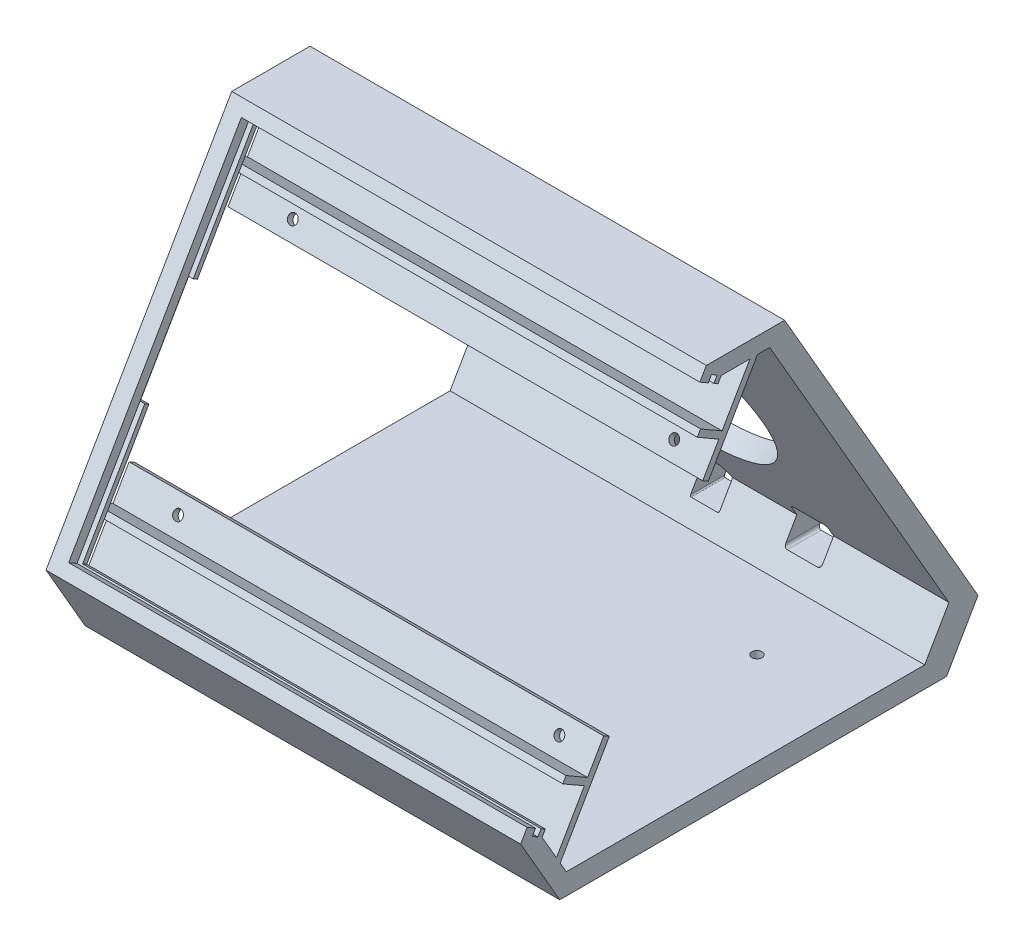
SolidWorks part; units mm, degrees
ref_plane "Front Plane" through (0, 0, 0) normal (0, 0, 1) x (1, 0, 0)
ref_plane "Top Plane" through (0, 0, 0) normal (0, 1, 0) x (1, 0, 0)
ref_plane "Right Plane" through (0, 0, 0) normal (1, 0, 0) x (0, 0, -1)
sketch "Sketch3" plane through (0, 0, 0) normal (1, 0, 0) x (0, 0, -1)
  line L0 (0, 0) -> (141, 0) construction
  line L1 (141, 0) -> (70.5, 122.1096) construction
  line L2 (70.5, 122.1096) -> (0, 0) construction
  line L3 (7.5, 12.9904) -> (15, 0)
  line L4 (7.5, 12.9904) -> (0, 0) construction
  line L5 (0, 0) -> (15, 0) construction
  line L6 (15, 0) -> (15, -1.5)
  line L7 (15, -1.5) -> (126, -1.5)
  line L8 (70.5, 122.1096) -> (70.5, 0) construction
  line L9 (133.5, 12.9904) -> (126, 0)
  line L10 (126, -1.5) -> (126, 0)
  line L11 (7.5, 12.9904) -> (6.201, 13.7404)
  line L12 (6.201, 13.7404) -> (61.701, 109.8692)
  line L13 (61.701, 109.8692) -> (63, 109.1192)
  line L14 (63, 109.1192) -> (78, 109.1192)
  line L15 (79.299, 109.8692) -> (134.799, 13.7404)
  line L16 (134.799, 13.7404) -> (133.5, 12.9904)
  line L17 (78, 109.1192) -> (79.299, 109.8692)
  line L18 (58.3812, 114.1192) -> (0.8605, 14.4904)
  line L19 (0.8605, 14.4904) -> (12.9793, -6.5)
  line L20 (12.9793, -6.5) -> (132.75, -6.5)
  line L21 (132.75, -6.5) -> (142.5042, 10.3947)
  line L22 (142.5042, 10.3947) -> (82.6188, 114.1192)
  line L23 (82.6188, 114.1192) -> (58.3812, 114.1192)
  line L24 (129.75, 6.4952) -> (137.6271, 1.9474) construction
  line L25 (70.5, -1.5) -> (70.5, -6.5) construction
  line L26 (78, 109.1192) -> (78, 114.1192) construction
  dimension "D1" = 141
  dimension "D2" = 1.5
  dimension "D3" = 111
  dimension "D4" = 15
  dimension "D5" = 5
  dimension "D6" = 5
  dimension "D7" = 5
  dimension "D8" = 5
  dimension "D9" = 5
  dimension "D10" = 9.0957
extrude "Boss-Extrude1" add sketch "Sketch3" along normal blind 155
sketch "Sketch4" plane through (0, 3.25, 5.6292) normal (0, 0.5, 0.866) x (1, 0, 0)
  line L0 (155, 126) -> (0, 126) construction
  line L1 (5.5, 126) -> (149.5, 126)
  line L2 (5.5, 126) -> (5.5, 15)
  line L3 (5.5, 15) -> (149.5, 15)
  line L4 (149.5, 126) -> (149.5, 15)
  line L5 (155, 15) -> (0, 15) construction
  line L6 (5.5, 70.5) -> (0, 70.5) construction
  line L7 (0, 128.0207) -> (0, 12.9793) construction
  line L8 (149.5, 70.5) -> (155, 70.5) construction
  line L9 (155, 128.0207) -> (155, 12.9793) construction
  dimension "D1" = 144
extrude "Cut-Extrude1" cut sketch "Sketch4" against normal up to surface (5 mm away) up to face at (77.5, 61.8048, -33.951)
sketch "Sketch5" plane through (0, 64.3048, -111.3792) normal (0, 0.5, -0.866) x (-1, 0, 0)
  line L0 (-155, -62.25) -> (-77.5, -2.3646) construction
  line L1 (-77.5, -2.3646) -> (-155, 57.5207) construction
  line L2 (0, 57.5207) -> (-77.5, -2.3646) construction
  line L3 (-77.5, -2.3646) -> (0, -62.25) construction
  circle A0 centre (-77.5, -2.3646) radius 38.5
  dimension "D1" = 77
extrude "Cut-Extrude2" cut sketch "Sketch5" against normal blind 10
sketch "Sketch6" plane through (155, 0, 0) normal (1, 0, 0) x (0, 0, -1)
  line L6 (82.6188, 114.1192) -> (58.3812, 114.1192)
  line L7 (58.3812, 114.1192) -> (0.8605, 14.4904)
  line L8 (0.8605, 14.4904) -> (12.9793, -6.5)
  line L9 (12.9793, -6.5) -> (132.75, -6.5)
  line L10 (132.75, -6.5) -> (142.5042, 10.3947)
  line L11 (142.5042, 10.3947) -> (82.6188, 114.1192)
  line L12 (82.6188, 114.1192) -> (58.3812, 114.1192)
  line L13 (58.3812, 114.1192) -> (0.8605, 14.4904)
  line L14 (0.8605, 14.4904) -> (12.9793, -6.5)
  line L15 (12.9793, -6.5) -> (132.75, -6.5)
  line L16 (132.75, -6.5) -> (142.5042, 10.3947)
  line L17 (142.5042, 10.3947) -> (82.6188, 114.1192)
  dimension "D1" = 0
extrude "Boss-Extrude2" add sketch "Sketch6" along normal blind 5 separate body
sketch "Sketch7" plane through (160, 0, 0) normal (1, 0, 0) x (0, 0, -1)
  line L2 (78, 109.1192) -> (63, 109.1192) construction
  line L4 (126, 0) -> (133.5, 12.9904) construction
  line L20 (7.5, 12.9904) -> (15, 0) construction
  line L23 (63, 109.1192) -> (7.5, 12.9904)
  line L24 (15, 0) -> (126, 0)
  line L25 (78, 109.1192) -> (63, 109.1192)
  line L26 (133.5, 12.9904) -> (78, 109.1192)
  line L27 (126, 0) -> (133.5, 12.9904)
  line L31 (7.5, 12.9904) -> (15, 0)
extrude "Cut-Extrude3" cut sketch "Sketch7" against normal blind 5
sketch "Sketch8" plane through (160, 0, 0) normal (1, 0, 0) x (0, 0, -1)
  line L0 (6.201, 13.7404) -> (61.701, 109.8692)
  line L1 (61.701, 109.8692) -> (59.9689, 110.8692)
  line L3 (59.9689, 110.8692) -> (4.4689, 14.7404)
  line L5 (4.4689, 14.7404) -> (6.201, 13.7404)
  dimension "D1" = 2
extrude "Cut-Extrude4" cut sketch "Sketch8" against normal blind 2.5
sketch "Sketch10" plane through (160, 0, 0) normal (1, 0, 0) x (0, 0, -1)
  line L0 (35.25, 61.0548) -> (29.6208, 64.3048) construction
  line L1 (63, 109.1192) -> (7.5, 12.9904) construction
  line L2 (58.3812, 114.1192) -> (0.8605, 14.4904) construction
  line L3 (42.75, 74.0452) -> (27.75, 48.0644)
  line L4 (27.75, 48.0644) -> (26.451, 48.8144)
  line L5 (6.201, 13.7404) -> (61.701, 109.8692) construction
  line L6 (26.451, 48.8144) -> (41.451, 74.7952)
  line L7 (42.75, 74.0452) -> (41.451, 74.7952)
  point P13 (33.951, 61.8048)
  dimension "D1" = 30
extrude "Cut-Extrude5" cut sketch "Sketch10" against normal blind 2.5
sketch "Sketch11" plane through (160, 0, 0) normal (1, 0, 0) x (0, 0, -1)
  line L0 (63, 109.1192) -> (62, 107.3872)
  line L1 (63, 109.1192) -> (42.75, 74.0452) construction
  line L2 (7.5, 12.9904) -> (8.5, 14.7224)
  line L3 (27.75, 48.0644) -> (7.5, 12.9904) construction
  line L4 (0.8605, 14.4904) -> (12.9793, -6.5) construction
  line L5 (7.5, 12.9904) -> (15, 0) construction
  line L6 (15, 0) -> (126, 0) construction
  line L7 (12.9793, -6.5) -> (132.75, -6.5) construction
  line L8 (126, 0) -> (133.5, 12.9904) construction
  line L9 (132.75, -6.5) -> (142.5042, 10.3947) construction
  line L10 (142.5042, 10.3947) -> (82.6188, 114.1192) construction
  line L11 (133.5, 12.9904) -> (78, 109.1192) construction
  line L12 (82.6188, 114.1192) -> (58.3812, 114.1192) construction
  line L13 (78, 109.1192) -> (63, 109.1192) construction
  line L14 (0.8605, 14.4904) -> (12.9793, -6.5)
  line L15 (7.5, 12.9904) -> (15, 0)
  line L16 (15, 0) -> (126, 0)
  line L17 (12.9793, -6.5) -> (132.75, -6.5)
  line L18 (126, 0) -> (133.5, 12.9904)
  line L19 (132.75, -6.5) -> (142.5042, 10.3947)
  line L20 (142.5042, 10.3947) -> (82.6188, 114.1192)
  line L21 (133.5, 12.9904) -> (78, 109.1192)
  line L22 (82.6188, 114.1192) -> (58.3812, 114.1192)
  line L23 (78, 109.1192) -> (63, 109.1192)
  line L24 (62, 107.3872) -> (60.701, 108.1372)
  line L25 (41.451, 74.7952) -> (61.701, 109.8692) construction
  line L26 (60.701, 108.1372) -> (61.701, 109.8692)
  line L27 (61.701, 109.8692) -> (59.9689, 110.8692)
  line L28 (59.9689, 110.8692) -> (58.9689, 109.1372)
  line L29 (59.9689, 110.8692) -> (4.4689, 14.7404) construction
  line L30 (58.9689, 109.1372) -> (56.3708, 110.6372)
  line L31 (58.3812, 114.1192) -> (0.8605, 14.4904) construction
  line L32 (56.3708, 110.6372) -> (58.3812, 114.1192)
  line L33 (8.5, 14.7224) -> (7.201, 15.4724)
  line L34 (6.201, 13.7404) -> (26.451, 48.8144) construction
  line L35 (7.201, 15.4724) -> (6.201, 13.7404)
  line L36 (6.201, 13.7404) -> (4.4689, 14.7404)
  line L37 (4.4689, 14.7404) -> (5.4689, 16.4724)
  line L38 (5.4689, 16.4724) -> (2.8708, 17.9724)
  line L39 (2.8708, 17.9724) -> (0.8605, 14.4904)
  dimension "D1" = 2
extrude "Boss-Extrude3" add sketch "Sketch11" along normal blind 142
sketch "Sketch12" plane through (0, 64.3048, -111.3792) normal (0, 0.5, -0.866) x (-1, 0, 0)
  line L0 (-232.5, -2.3646) -> (-155, -2.3646) construction
  line L1 (-155, -62.25) -> (-155, 57.5207) construction
  line L2 (-77.5, -2.3646) -> (-155, -2.3646) construction
  circle A0 centre (-232.5, -2.3646) radius 38.5
  circle A1 centre (-77.5, -2.3646) radius 38.5 construction
extrude "Cut-Extrude6" cut sketch "Sketch12" against normal up to next (6.5 mm away)
delete or keep bodies "Body-Delete1" type delete bodies bodies 103
sketch "Sketch13" plane through (155, 0, 0) normal (-1, 0, 0) x (0, 0, 1)
  line L0 (-26.5934, 30.6611) -> (-21.5934, 22.0009)
  line L3 (-21.5934, 22.0009) -> (-14.925, 25.8509)
  line L4 (-63, 109.1192) -> (-7.5, 12.9904) construction
  line L5 (-26.5934, 30.6611) -> (-28.3254, 29.6611)
  line L8 (-28.3254, 29.6611) -> (-13.1003, 3.2904)
  line L11 (-7.5, 12.9904) -> (-15, 0) construction
  line L12 (-14.925, 25.8509) -> (-13.925, 24.1188)
  line L13 (-13.925, 24.1188) -> (-20.5934, 20.2688)
  line L14 (-20.5934, 20.2688) -> (-11.9456, 5.2904)
  line L15 (-11.9456, 5.2904) -> (-13.1003, 3.2904)
  line L16 (-62.2434, 92.4087) -> (-55.575, 96.2587)
  line L17 (-62.2434, 92.4087) -> (-57.2434, 83.7485)
  line L18 (-57.2434, 83.7485) -> (-58.9754, 82.7485)
  line L19 (-58.9754, 82.7485) -> (-74.2006, 109.1192)
  line L20 (-55.575, 96.2587) -> (-56.575, 97.9908)
  line L21 (-56.575, 97.9908) -> (-63.2434, 94.1408)
  line L22 (-63.2434, 94.1408) -> (-71.8912, 109.1192)
  line L23 (-78, 109.1192) -> (-63, 109.1192) construction
  line L24 (-74.2006, 109.1192) -> (-71.8912, 109.1192)
  line L25 (-56.575, 97.9908) -> (-63, 109.1192) construction
  line L26 (-13.925, 24.1188) -> (-7.5, 12.9904) construction
  dimension "D1" = 10
  dimension "D2" = 2
  dimension "D3" = 81.3
  dimension "D4" = 7.7
extrude "Boss-Extrude4" add sketch "Sketch13" along direction (-1, 0, 0) on the side against the normal up to surface (147 mm away)
ref_plane "Plane1" through (0, 0, -150) normal (0, 0, 1) x (1, 0, 0)
sketch "Sketch14" plane through (0, 0, -150) normal (0, 0, 1) x (1, 0, 0)
  line L0 (234.6666, 5.5875) -> (226.437, 5.5875) construction
  line L1 (234.6666, 5.5875) -> (226.437, 5.5875)
  line L2 (235.0476, 12.0391) -> (235.0476, 5.9685)
  line L3 (226.056, 12.0391) -> (226.056, 5.9685)
  line L4 (265.2999, 6.0875) -> (255.8999, 6.0875)
  line L5 (254.8999, 7.0875) -> (254.8999, 15.5875)
  line L7 (255.8999, 16.5875) -> (265.2999, 16.5875)
  line L8 (266.2999, 15.5875) -> (266.2999, 7.0875)
  line L9 (265.7999, 16.5875) -> (255.3999, 16.5875) construction
  arc A0 (235.0476, 12.0391) -> (226.056, 12.0391) centre (230.5518, 12.0391) ccw construction
  arc A1 (235.0476, 12.0391) -> (226.056, 12.0391) centre (230.5518, 12.0391) ccw
  arc A2 (226.056, 5.9685) -> (226.437, 5.5875) centre (226.437, 5.9685) ccw construction
  arc A3 (234.6666, 5.5875) -> (235.0476, 5.9685) centre (234.6666, 5.9685) ccw construction
  arc A4 (226.056, 5.9685) -> (226.437, 5.5875) centre (226.437, 5.9685) ccw
  arc A5 (234.6666, 5.5875) -> (235.0476, 5.9685) centre (234.6666, 5.9685) ccw
  arc A7 (266.2999, 7.0875) -> (265.2999, 6.0875) centre (265.2999, 7.0875) cw
  arc A8 (255.8999, 6.0875) -> (254.8999, 7.0875) centre (255.8999, 7.0875) cw
  arc A9 (254.8999, 15.5875) -> (255.8999, 16.5875) centre (255.8999, 15.5875) cw
  arc A10 (265.2999, 16.5875) -> (266.2999, 15.5875) centre (265.2999, 15.5875) cw
  point P19 (266.2999, 6.0875)
  point P22 (254.8999, 6.0875)
  dimension "D1" = 1
extrude "Cut-Extrude7" cut sketch "Sketch14" along normal blind 25
ref_plane "Plane2" through (167.5268, 23.1509, -19.6015) normal (0, -0.866, 0.5) x (1, 0, 0)
sketch "Sketch16" plane through (0, -4.85, -8.4004) normal (0, -0.5, -0.866) x (-1, 0, 0)
  circle A0 centre (-172.6068, 106.05) radius 1.5 construction
  circle A1 centre (-172.6068, 106.05) radius 1.5
  circle A2 centre (-172.6068, 34.95) radius 1.5 construction
  circle A3 centre (-290.7168, 106.05) radius 1.5 construction
  circle A4 centre (-290.7168, 34.95) radius 1.5 construction
  circle A5 centre (-172.6068, 34.95) radius 1.5
  circle A6 centre (-290.7168, 106.05) radius 1.5
  circle A7 centre (-290.7168, 34.95) radius 1.5
extrude "Cut-Extrude8" cut sketch "Sketch16" against normal blind 5
sketch "Sketch17" plane through (0, 0, 0) normal (0, 1, 0) x (1, 0, 0)
  circle A0 centre (230.12, 51.9601) radius 1.5875 construction
  circle A1 centre (258.06, 51.9601) radius 1.5875 construction
  circle A2 centre (273.3, 102.7601) radius 1.5875 construction
  circle A3 centre (230.12, 51.9601) radius 1.5875
  circle A4 centre (258.06, 51.9601) radius 1.5875
  circle A5 centre (273.3, 102.7601) radius 1.5875
extrude "Cut-Extrude9" cut sketch "Sketch17" against normal blind 10
